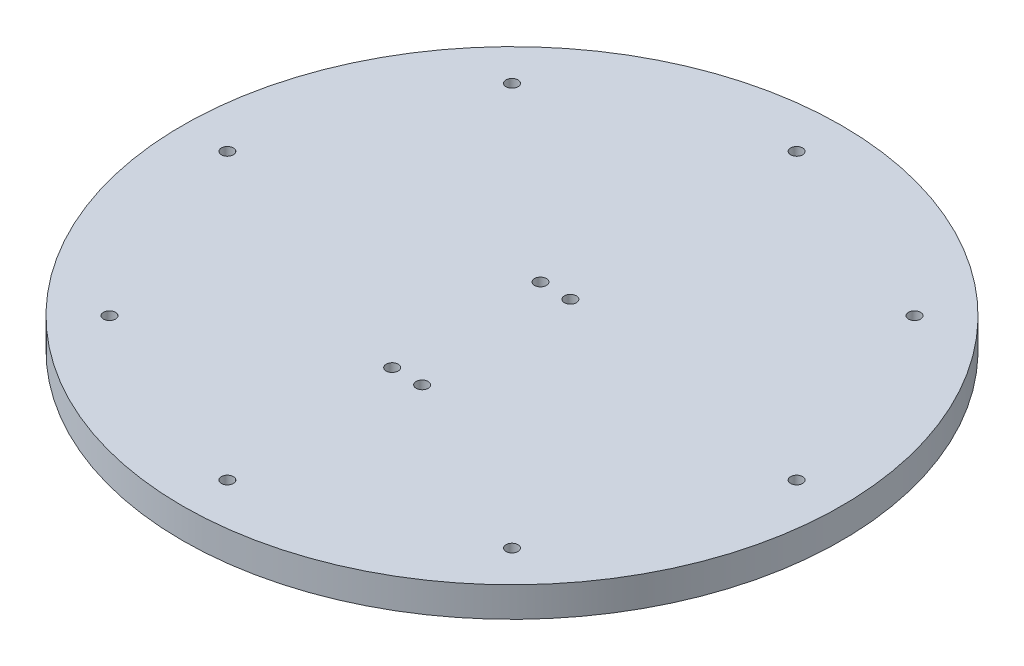
SolidWorks part; units mm, degrees
ref_plane "Front Plane" through (0, 0, 0) normal (0, 0, 1) x (1, 0, 0)
ref_plane "Top Plane" through (0, 0, 0) normal (0, 1, 0) x (1, 0, 0)
ref_plane "Right Plane" through (0, 0, 0) normal (1, 0, 0) x (0, 0, -1)
sketch "Sketch2" plane through (0, 0, 0) normal (0, 1, 0) x (1, 0, 0)
  circle A1 centre (0, 0) radius 110
  point P23 (0, 0)
extrude "Boss-Extrude2" add sketch "Sketch2" along normal blind 10
sketch "Sketch3" plane through (0, 10, 0) normal (0, 1, 0) x (1, 0, 0)
  line L0 (0, 0) -> (0, 126.7719) construction
  circle A0 centre (0, 95) radius 2
  circle A1 centre (67.1751, 67.1751) radius 2
  circle A2 centre (95, 0) radius 2
  circle A3 centre (67.1751, -67.1751) radius 2
  circle A4 centre (0, -95) radius 2
  circle A5 centre (-67.1751, -67.1751) radius 2
  circle A6 centre (-95, 0) radius 2
  circle A7 centre (-67.1751, 67.1751) radius 2
  point P21 (0, 0)
  dimension "D1" = 4
  dimension "D2" = 95
  dimension "D3" = 8
extrude "Cut-Extrude1" cut sketch "Sketch3" against normal blind 10
sketch "Sketch4" plane through (0, 0, 0) normal (0, 1, 0) x (1, 0, 0)
  circle A0 centre (0, 95) radius 5
  circle A1 centre (67.1751, 67.1751) radius 5
  circle A2 centre (95, 0) radius 5
  circle A3 centre (67.1751, -67.1751) radius 5
  circle A4 centre (0, -95) radius 5
  circle A5 centre (-67.1751, -67.1751) radius 5
  circle A6 centre (-95, 0) radius 5
  circle A7 centre (-67.1751, 67.1751) radius 5
  point P19 (0, 0)
  dimension "D1" = 10
  dimension "D2" = 8
extrude "Cut-Extrude2" cut sketch "Sketch4" along normal blind 6
sketch "Sketch5" plane through (0, 10, 0) normal (0, 1, 0) x (1, 0, 0)
  circle A0 centre (5, 14.5) radius 2
  circle A1 centre (-5, 14.5) radius 2
  circle A2 centre (5, -35) radius 2
  circle A3 centre (-5, -35) radius 2
  dimension "D1" = 4
  dimension "D2" = 4
  dimension "D3" = 4
  dimension "D4" = 4
  dimension "D5" = 14.5
  dimension "D6" = 14.5
  dimension "D7" = 5
  dimension "D8" = 5
  dimension "D9" = 35
  dimension "D10" = 35
  dimension "D11" = 5
  dimension "D12" = 5
extrude "Cut-Extrude3" cut sketch "Sketch5" against normal through all
sketch "Sketch7" plane through (0, 0, 0) normal (0, -1, 0) x (1, 0, 0)
  circle A0 centre (5, 35) radius 5
  circle A1 centre (-5, 35) radius 5
  circle A2 centre (5, -14.5) radius 4.5
  circle A3 centre (-5, -14.5) radius 4.5
  circle M3 centre (-5, -14.5) radius 2
  circle M6 centre (5, -14.5) radius 2
  dimension "D1" = 10
  dimension "D2" = 10
  dimension "D3" = 9
  dimension "D4" = 9
extrude "Cut-Extrude9" cut sketch "Sketch7" against normal blind 6 contours A2 M6 | A3 M3
sketch "Sketch8" plane through (0, 0, 0) normal (0, -1, 0) x (1, 0, 0)
  circle A0 centre (5, 35) radius 4.5
  circle A1 centre (-5, 35) radius 4.5
  dimension "D1" = 9
  dimension "D2" = 9
extrude "Cut-Extrude10" cut sketch "Sketch8" against normal blind 6
